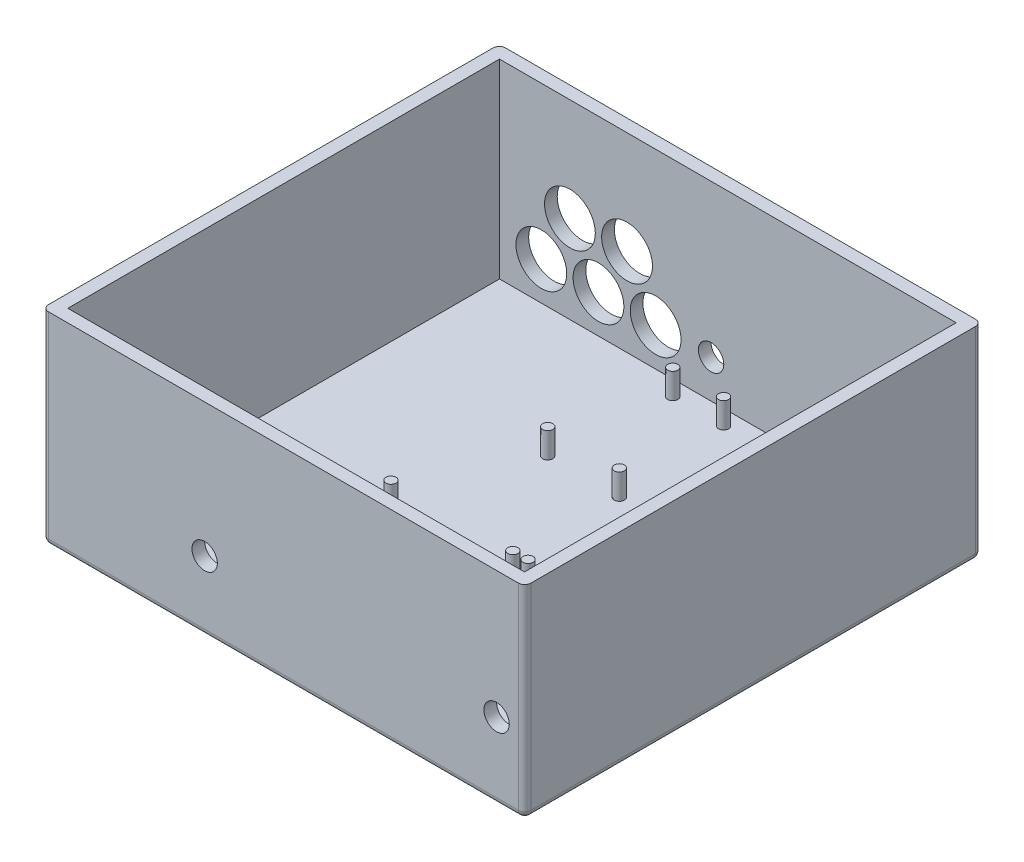
SolidWorks part; units mm, degrees
ref_plane "Front Plane" through (0, 0, 0) normal (0, 0, 1) x (1, 0, 0)
ref_plane "Top Plane" through (0, 0, 0) normal (0, 1, 0) x (1, 0, 0)
ref_plane "Right Plane" through (0, 0, 0) normal (1, 0, 0) x (0, 0, -1)
sketch "Sketch3" plane through (0, 0, 0) normal (0, 1, 0) x (1, 0, 0)
  line L1 (-120.65, -114.3) -> (120.65, -114.3)
  line L2 (-120.65, -114.3) -> (-120.65, 114.3)
  line L3 (-120.65, 114.3) -> (120.65, 114.3)
  line L4 (120.65, -114.3) -> (120.65, 114.3)
  line L5 (-120.65, -114.3) -> (120.65, 114.3) construction
  line L6 (-120.65, 114.3) -> (120.65, -114.3) construction
  point P0 (0, 0)
  dimension "D1" = 241.3
  dimension "D2" = 228.6
extrude "Boss-Extrude2" add sketch "Sketch3" along normal blind 101.6 contours L2 L3 L4 L1
sketch "Sketch5" plane through (0, 101.6, 0) normal (0, 1, 0) x (1, 0, 0)
  line L0 (-120.65, 114.3) -> (120.65, 114.3) construction
  line L1 (-114.2093, -107.95) -> (114.2093, -107.95)
  line L2 (-114.2093, -107.95) -> (-114.2093, 107.95)
  line L3 (-114.2093, 107.95) -> (114.2093, 107.95)
  line L4 (114.2093, -107.95) -> (114.2093, 107.95)
  line L5 (-114.2093, -107.95) -> (114.2093, 107.95) construction
  line L6 (-114.2093, 107.95) -> (114.2093, -107.95) construction
  line L7 (-120.65, -114.3) -> (-120.65, 114.3) construction
  point P0 (0, 0)
  dimension "D1" = 6.35
  dimension "D2" = 6.4407
extrude "Cut-Extrude1" cut sketch "Sketch5" against normal offset from surface (95.25 mm away) 6.35 contours L2 L3 L4 L1 up to face at (0, 0, 0)
fillet "Fillet1" radius 3.175 8 edges at (-120.65, 50.8, -114.3) (-120.65, 50.8, 114.3) (0, 0, -114.3) (120.65, 50.8, 114.3) (-120.65, 0, 0) (120.65, 50.8, -114.3) (120.65, 0, 0) (0, 0, 114.3)
sketch "Sketch9" plane through (0, 6.35, 0) normal (0, 1, 0) x (1, 0, 0)
  line L0 (114.2093, 107.95) -> (114.2093, -107.95) construction
  line L1 (-114.2093, -107.95) -> (-114.2093, 107.95) construction
  line L2 (-114.2093, 107.95) -> (114.2093, 107.95) construction
  line L3 (114.2093, -107.95) -> (-114.2093, -107.95) construction
  line L4 (-114.2093, -107.95) -> (114.2093, -107.95) construction
  circle A0 centre (19.4673, -19.05) radius 2.54
  circle A1 centre (27.0873, -19.05) radius 2.54
  circle A2 centre (-41.4927, -19.05) radius 2.54
  circle A3 centre (107.8593, -19.05) radius 2.54
  circle A4 centre (107.8593, 44.45) radius 2.54
  circle A5 centre (-107.8593, -101.6) radius 2.54
  circle A6 centre (-60.2343, -44.958) radius 2.54
  circle A7 centre (-107.8593, -44.958) radius 2.54
  circle A8 centre (-60.2343, -101.6) radius 2.54
  circle A9 centre (-25.5129, 43.3841) radius 2.54
  circle A10 centre (-19.9249, 100.33) radius 2.54
  circle A11 centre (10.3011, 43.3841) radius 2.54
  circle A12 centre (5.4751, 100.33) radius 2.54
  point P37 (0, 0)
  dimension "D1" = 5.08
  dimension "D2" = 7.62
  dimension "D3" = 0
  dimension "D4" = 60.96
  dimension "D5" = 80.772
  dimension "D6" = 63.5
  dimension "D7" = 0
  dimension "D9" = 5.08
  dimension "D10" = 0
  dimension "D11" = 47.625
  dimension "D12" = 56.642
  dimension "D13" = 0
  dimension "D14" = 47.625
  dimension "D15" = 0
  dimension "D16" = 6.35
  dimension "D17" = 6.35
  dimension "D18" = 5.08
  dimension "D21" = 57.15
  dimension "D20" = 0
  dimension "D22" = 25.4
  dimension "D23" = 4.826
  dimension "D24" = 0
  dimension "D25" = 57.2194
  dimension "D26" = 7.62
  dimension "D27" = 88.9
  dimension "D8" = 6.35
  dimension "D19" = 35.814
sketch "Sketch10" plane through (0, 6.35, 0) normal (0, 1, 0) x (1, 0, 0)
sketch "Sketch14" plane through (0, 6.35, 0) normal (0, 1, 0) x (1, 0, 0)
sketch "Sketch15" plane through (0, 6.35, 0) normal (0, 1, 0) x (1, 0, 0)
ref_plane "Plane1" through (-114.2093, 101.6, 107.95) normal (0, 0, -1) x (-1, 0, 0)
sketch "Sketch18" plane through (0, 0, -107.95) normal (0, 0, 1) x (1, 0, 0)
  line L0 (114.2093, 6.35) -> (-114.2093, 6.35) construction
  circle A0 centre (-8.3722, 25.4) radius 6.35
  circle A1 centre (-36.1215, 25.4) radius 12.7
  circle A2 centre (-64.6965, 25.4) radius 12.7
  circle A3 centre (-93.2715, 25.4) radius 12.7
  circle A4 centre (-78.984, 50.1467) radius 12.7
  circle A5 centre (-50.409, 50.1467) radius 12.7
  circle A6 centre (82.3164, 34.0913) radius 15.3471
  point P14 (49.6709, 70.3112)
  dimension "D1" = 12.7
  dimension "D2" = 19.05
  dimension "D3" = 25.4
  dimension "D4" = 28.575
  dimension "D5" = 28.575
  dimension "D6" = 0
  dimension "D7" = 0
  dimension "D8" = 0
  dimension "D9" = 28.575
  dimension "D10" = 28.575
  dimension "D11" = 28.575
  dimension "D12" = 28.575
sketch "Sketch20" plane through (-120.65, 0, 0) normal (-1, 0, 0) x (0, 0, 1)
extrude "Cut-Extrude5" cut sketch "Sketch18" against normal blind 8.89 contours A0 | A1 | A5 | A2 | A3 | A4
extrude "Boss-Extrude12" add sketch "Sketch9" along normal blind 12.7
sketch "Sketch27" plane through (0, 0, 114.3) normal (0, 0, 1) x (1, 0, 0)
  line L0 (114.2093, 6.35) -> (114.2093, 101.6) construction
  line L1 (114.2093, 6.35) -> (-114.2093, 6.35) construction
  circle A0 centre (-39.4243, 34.841) radius 6.35
  circle A1 centre (106.5893, 38.1) radius 6.35
  dimension "D1" = 12.7
  dimension "D2" = 146.05
  dimension "D3" = 7.62
  dimension "D4" = 31.75
extrude "Cut-Extrude6" cut sketch "Sketch27" against normal blind 8.89
